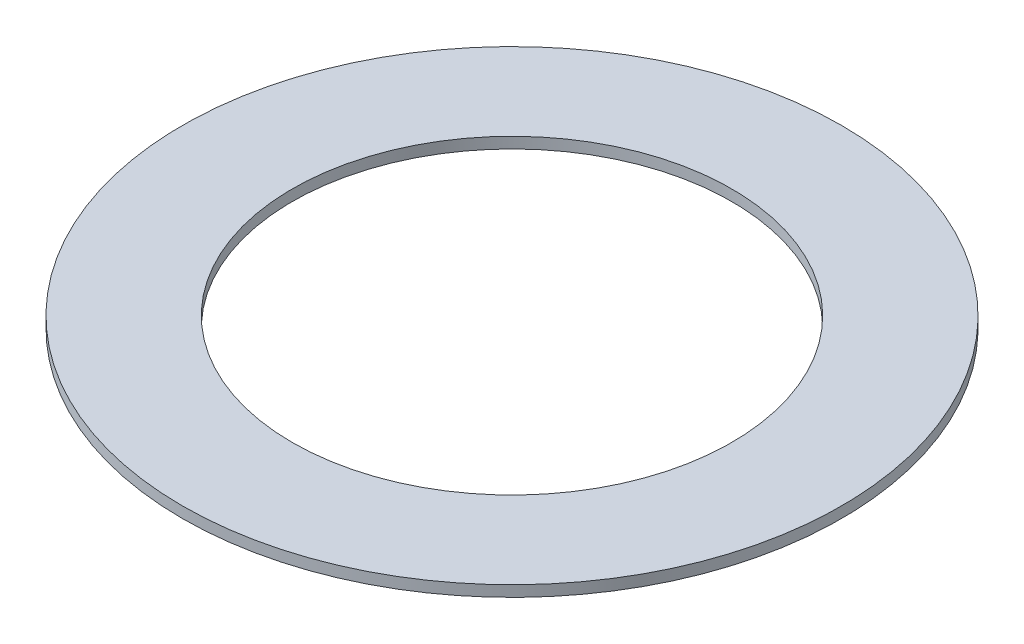
SolidWorks part; units mm, degrees
ref_plane "Front Plane" through (0, 0, 0) normal (0, 0, 1) x (1, 0, 0)
ref_plane "Top Plane" through (0, 0, 0) normal (0, 1, 0) x (1, 0, 0)
ref_plane "Right Plane" through (0, 0, 0) normal (1, 0, 0) x (0, 0, -1)
sketch "Sketch1" plane through (0, 0, 0) normal (0, 1, 0) x (1, 0, 0)
  circle A0 centre (0, 0) radius 20
  circle A1 centre (0, 0) radius 30
  dimension "D1" = 40
  dimension "D2" = 60
extrude "Boss-Extrude1" add sketch "Sketch1" along normal blind 1
